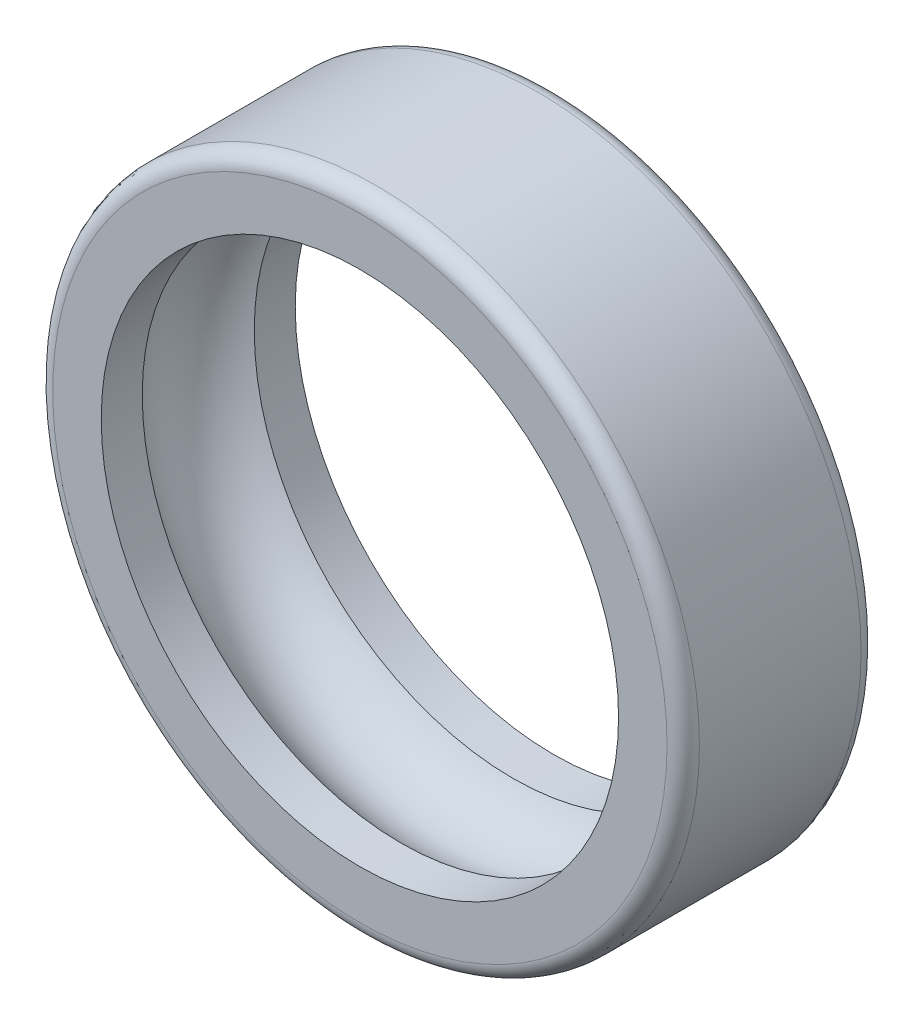
SolidWorks part; units mm, degrees
ref_plane "Front Plane" through (0, 0, 0) normal (0, 0, 1) x (1, 0, 0)
ref_plane "Top Plane" through (0, 0, 0) normal (0, 1, 0) x (1, 0, 0)
ref_plane "Right Plane" through (0, 0, 0) normal (1, 0, 0) x (0, 0, -1)
sketch "Sketch1" plane through (0, 0, 0) normal (0, 0, 1) x (1, 0, 0)
  circle A0 centre (0, 0) radius 10
  circle A1 centre (0, 0) radius 8
  dimension "D1" = 20
  dimension "D2" = 16
extrude "Boss-Extrude1" add sketch "Sketch1" along normal mid plane 6
sketch "Sketch2" plane through (0, 0, 0) normal (0, 1, 0) x (1, 0, 0)
  line L0 (-3.5218, 0) -> (3.8897, 0) construction
  line L1 (0, 1.8003) -> (0, -1.6952) construction
  circle A0 centre (-7, 0) radius 2
  point P7 (0, 0)
  dimension "D1" = 4
  dimension "D2" = 7
revolve "Cut-Revolve1" cut sketch "Sketch2" angle 360 about L1
fillet "Fillet1" radius 0.5 2 edges at (10, 0, -3) (10, 0, 3)
